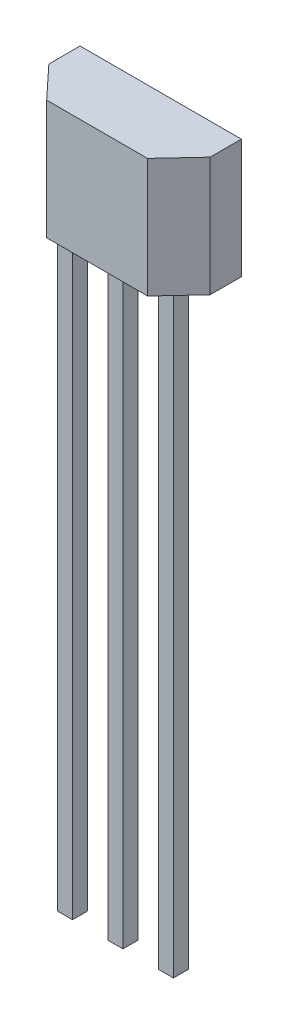
SolidWorks part; units mm, degrees
ref_plane "Front Plane" through (0, 0, 0) normal (0, 0, 1) x (1, 0, 0)
ref_plane "Top Plane" through (0, 0, 0) normal (0, 1, 0) x (1, 0, 0)
ref_plane "Right Plane" through (0, 0, 0) normal (1, 0, 0) x (0, 0, -1)
sketch "PROF_TOP_VIEW" plane through (0, 0, 0) normal (0, 1, 0) x (1, 0, 0)
  line L0 (-2.03, 0) -> (2.03, 0)
  line L1 (-2.03, 0) -> (-2.03, -0.785)
  line L2 (-2.03, -0.785) -> (-1.27, -1.6)
  line L3 (-1.27, -1.6) -> (1.27, -1.6)
  line L4 (1.27, -1.6) -> (2.03, -0.785)
  line L5 (2.03, -0.785) -> (2.03, 0)
  line L6 (0, 0) -> (0, -1.6) construction
  point P9 (1.1654, -1.6)
  point P10 (0, 0)
  point P11 (0, 0)
  dimension "D1" = 4.06
  dimension "D2" = 1.6
  dimension "D3" = 47
  dimension "D4" = 2.54
sketch "PROF_BACK_VIEW" plane through (0, 0, 0) normal (0, 0, 1) x (1, 0, 0)
  line L0 (-2.03, 0) -> (-1.27, 0) construction
  line L1 (-2.03, 0) -> (2.03, 0)
  line L2 (-2.03, 0) -> (-2.03, -3)
  line L3 (-2.03, -3) -> (2.03, -3)
  line L4 (2.03, 0) -> (2.03, -3)
  point P6 (2.5559, 0)
  point P9 (0, 0)
  dimension "D1" = 3
extrude "Boss-Extrude1" add sketch "PROF_TOP_VIEW" against normal up to vertex (3 mm away) up to point (-2.03, -3, 0)
sketch "Sketch3" plane through (0, -3, 0) normal (0, -1, 0) x (1, 0, 0)
  line L0 (0, 1.14) -> (0, 0) construction
  line L1 (-1.46, 1.14) -> (-1.08, 1.14)
  line L2 (-1.46, 1.14) -> (-1.46, 0.76)
  line L3 (-1.46, 0.76) -> (-1.08, 0.76)
  line L4 (-1.08, 1.14) -> (-1.08, 0.76)
  line L5 (-0.19, 1.14) -> (0.19, 1.14)
  line L6 (-0.19, 1.14) -> (-0.19, 0.76)
  line L7 (-0.19, 0.76) -> (0.19, 0.76)
  line L8 (0.19, 1.14) -> (0.19, 0.76)
  line L9 (1.08, 1.14) -> (1.46, 1.14)
  line L10 (1.08, 1.14) -> (1.08, 0.76)
  line L11 (1.08, 0.76) -> (1.46, 0.76)
  line L12 (1.46, 1.14) -> (1.46, 0.76)
  line L13 (-1.27, 1.14) -> (-1.27, 0.76) construction
  line L14 (-2.03, 0) -> (2.03, 0) construction
  dimension "D1" = 0.38
  dimension "D2" = 1.27
  dimension "D3" = 0.76
  dimension "D4" = 0.38
extrude "Boss-Extrude2" add sketch "Sketch3" along normal blind 15
